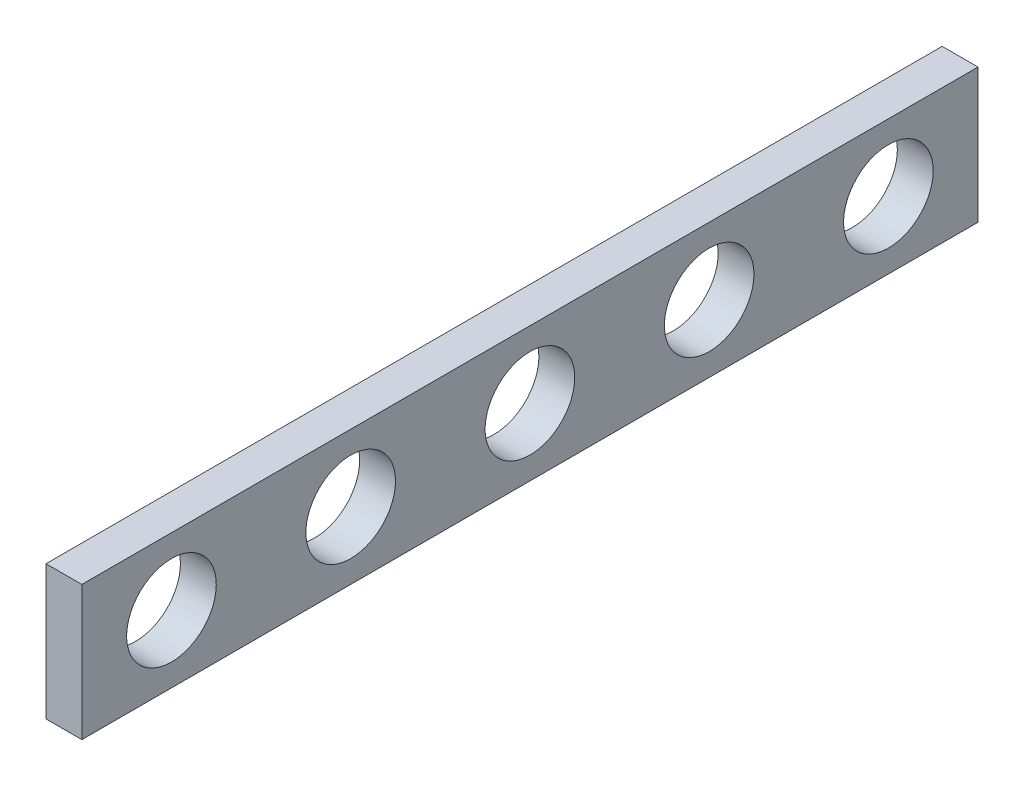
SolidWorks part; units mm, degrees
ref_plane "Front Plane" through (0, 0, 0) normal (0, 0, 1) x (1, 0, 0)
ref_plane "Top Plane" through (0, 0, 0) normal (0, 1, 0) x (1, 0, 0)
ref_plane "Right Plane" through (0, 0, 0) normal (1, 0, 0) x (0, 0, -1)
sketch "Sketch1" plane through (0, 0, 0) normal (1, 0, 0) x (0, 0, -1)
  line L1 (-250, -37.5) -> (250, -37.5)
  line L2 (-250, -37.5) -> (-250, 37.5)
  line L3 (-250, 37.5) -> (250, 37.5)
  line L4 (250, -37.5) -> (250, 37.5)
  line L5 (-250, -37.5) -> (250, 37.5) construction
  line L6 (-250, 37.5) -> (250, -37.5) construction
  circle A0 centre (0, 0) radius 25
  circle A1 centre (100, 0) radius 25
  circle A2 centre (200, 0) radius 25
  circle A3 centre (-100, 0) radius 25
  circle A4 centre (-200, 0) radius 25
  point P0 (0, 0)
  dimension "D3" = 50
  dimension "D1" = 500
  dimension "D2" = 75
  dimension "D4" = 3
  dimension "D5" = 3
extrude "Boss-Extrude1" add sketch "Sketch1" along normal blind 20
